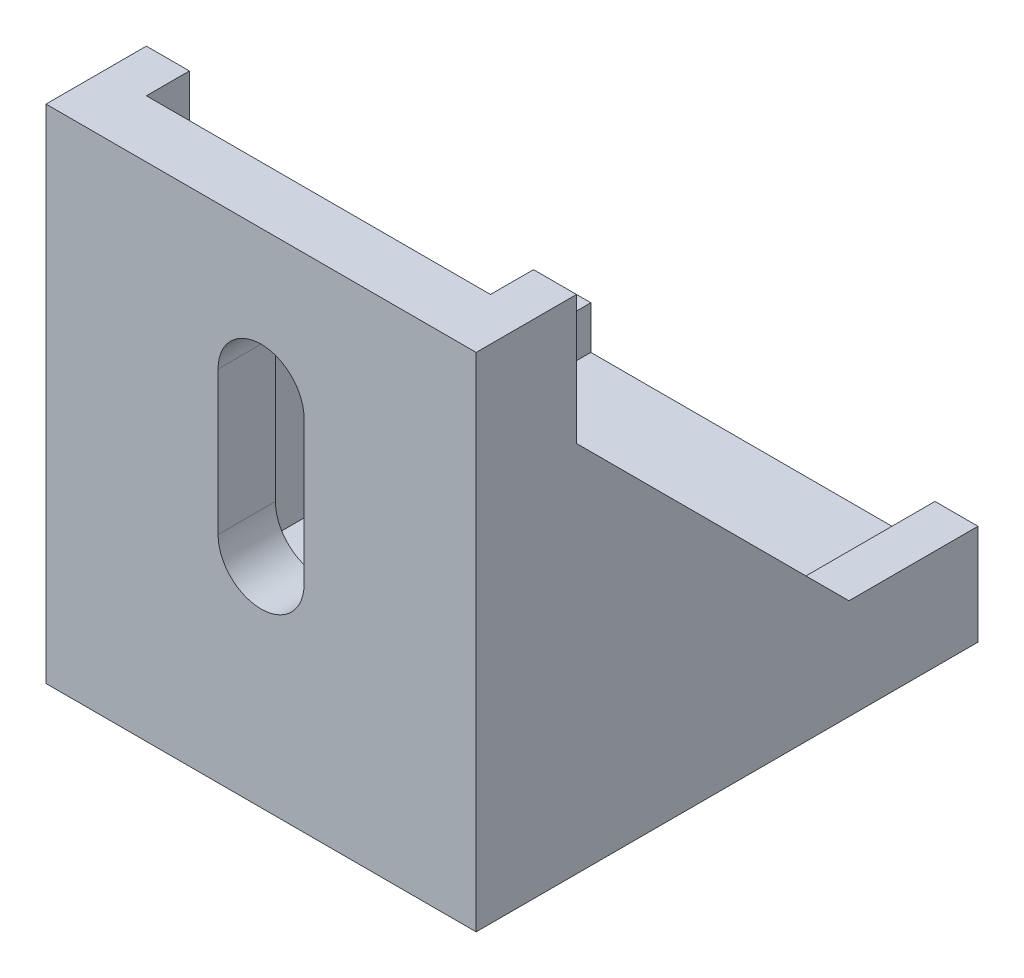
SolidWorks part; units mm, degrees
material "1060 Alloy"
ref_plane "Front Plane" through (0, 0, 0) normal (0, 0, 1) x (1, 0, 0)
ref_plane "Top Plane" through (0, 0, 0) normal (0, 1, 0) x (1, 0, 0)
ref_plane "Right Plane" through (0, 0, 0) normal (1, 0, 0) x (0, 0, -1)
sketch "Sketch2" plane through (0, 0, 0) normal (1, 0, 0) x (0, 0, -1)
  line L0 (0, 35) -> (0, 0)
  line L1 (0, 0) -> (35, 0)
  line L2 (35, 0) -> (35, 4)
  line L3 (35, 4) -> (4, 4)
  line L4 (4, 4) -> (4, 35)
  line L5 (4, 35) -> (0, 35)
  dimension "D1" = 35
  dimension "D2" = 35
  dimension "D3" = 4
  dimension "D4" = 31
extrude "Boss-Extrude1" add sketch "Sketch2" along normal blind 30
other "Gusset1" parameters "D1"=3, "D2"=3, "D3"=0, "D4"=0, "D10"=5, "D11"=25, "D12"=25, "D13"=15, "D14"=45, "D15"=15
sketch "Sketch5" plane through (30, 4, -4) normal (-1, 0, 0) x (0, 0, 1)
  line L0 (0, 0) -> (0, 25)
  line L1 (0, 0) -> (-25, 0)
  line L2 (0, 25) -> (-25, 0)
other "Gusset2" parameters "D1"=3, "D2"=3, "D3"=0, "D4"=0, "D10"=5, "D11"=25, "D12"=25, "D13"=15, "D14"=45, "D15"=15
sketch "Sketch6" plane through (0, 4, -4) normal (1, 0, 0) x (0, 0, -1)
  line L0 (0, 0) -> (25, 0)
  line L1 (0, 0) -> (0, 25)
  line L2 (25, 0) -> (0, 25)
sketch "Sketch7" plane through (30, 0, 0) normal (1, 0, 0) x (0, 0, -1)
  line L0 (4, 35) -> (7, 35)
  line L1 (7, 35) -> (7, 26)
  line L2 (4, 29) -> (29, 4) construction
  line L3 (7, 26) -> (4, 29)
  line L4 (4, 29) -> (4, 35)
  dimension "D1" = 3
extrude "Boss-Extrude2" add sketch "Sketch7" against normal blind 3
ref_plane "Plane1" through (15, 0, 0) normal (-1, 0, 0) x (0, 0, 1)
sketch "Sketch8" plane through (0, 0, 0) normal (-1, 0, 0) x (0, 0, 1)
  line L0 (-4, 35) -> (-7, 35)
  line L1 (-7, 35) -> (-4, 35) construction
  line L2 (-7, 35) -> (-7, 26)
  line L3 (-7, 26) -> (-4, 29)
  line L4 (-4, 4) -> (-4, 35) construction
  line L5 (-4, 35) -> (-4, 4) construction
  line L6 (-4, 29) -> (-4, 35)
extrude "Boss-Extrude3" add sketch "Sketch8" against normal blind 3
sketch "Sketch9" plane through (0, 0, 0) normal (-1, 0, 0) x (0, 0, 1)
  line L0 (-35, 4) -> (-35, 7)
  line L1 (-35, 7) -> (-26, 7)
  line L2 (-29, 4) -> (-7, 26) construction
  line L3 (-26, 7) -> (-29, 4)
  line L4 (-29, 4) -> (-35, 4)
  dimension "D1" = 3
extrude "Boss-Extrude4" add sketch "Sketch9" against normal blind 3
sketch "Sketch10" plane through (30, 0, 0) normal (1, 0, 0) x (0, 0, -1)
  line L0 (35, 4) -> (35, 7)
  line L1 (35, 7) -> (35, 4) construction
  line L2 (35, 7) -> (26, 7)
  line L3 (26, 7) -> (29, 4)
  line L4 (29, 4) -> (35, 4)
extrude "Boss-Extrude5" add sketch "Sketch10" against normal blind 3
sketch "Sketch11" plane through (0, 0, 0) normal (0, 0, 1) x (1, 0, 0)
  line L3 (15, 15) -> (15, 25) construction
  line L5 (12, 15) -> (12, 25)
  line L6 (18, 15) -> (18, 25)
  arc A0 (12, 15) -> (18, 15) centre (15, 15) ccw
  arc A1 (18, 25) -> (12, 25) centre (15, 25) ccw
  point P10 (15, 20)
extrude "Cut-Extrude1" cut sketch "Sketch11" against normal through all
sketch "Sketch12" plane through (0, 0, 0) normal (0, -1, 0) x (1, 0, 0)
  line L3 (15, -22.5) -> (15, -12.5) construction
  line L5 (12, -22.5) -> (12, -12.5)
  line L6 (18, -22.5) -> (18, -12.5)
  arc A0 (12, -22.5) -> (18, -22.5) centre (15, -22.5) ccw
  arc A1 (18, -12.5) -> (12, -12.5) centre (15, -12.5) ccw
  point P10 (15, -17.5)
extrude "Cut-Extrude2" cut sketch "Sketch12" against normal blind 13
